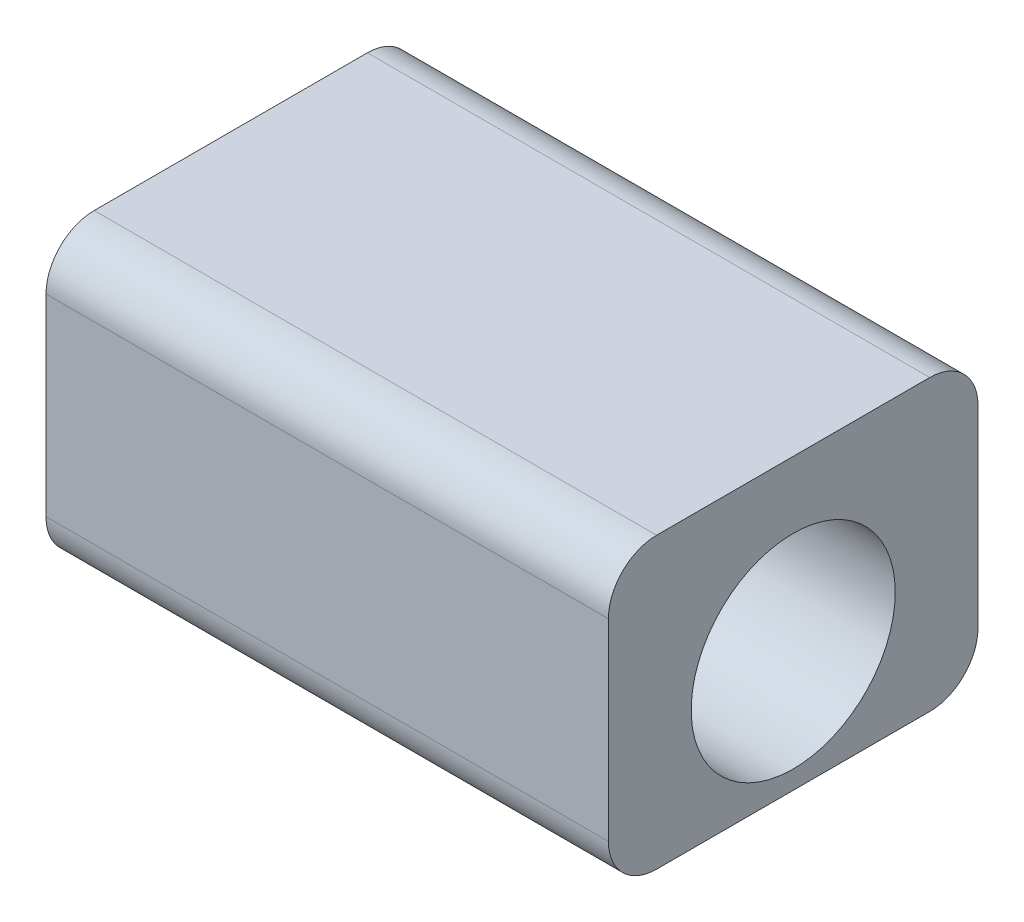
SolidWorks part; units mm, degrees
ref_plane "Front Plane" through (0, 0, 0) normal (0, 0, 1) x (1, 0, 0)
ref_plane "Top Plane" through (0, 0, 0) normal (0, 1, 0) x (1, 0, 0)
ref_plane "Right Plane" through (0, 0, 0) normal (1, 0, 0) x (0, 0, -1)
sketch "Sketch1" plane through (0, 0, 0) normal (1, 0, 0) x (0, 0, -1)
  line L0 (-17, -15) -> (17, -15)
  line L1 (23, -9) -> (23, 15)
  line L2 (17, 21) -> (-17, 21)
  line L3 (-23, 15) -> (-23, -9)
  arc A0 (17, -15) -> (23, -9) centre (17, -9) ccw
  arc A1 (23, 15) -> (17, 21) centre (17, 15) ccw
  arc A2 (-17, 21) -> (-23, 15) centre (-17, 15) ccw
  arc A3 (-23, -9) -> (-17, -15) centre (-17, -9) ccw
  circle A4 centre (0, 0) radius 12.7
extrude "Boss-Extrude1" add sketch "Sketch1" along normal mid plane 70
